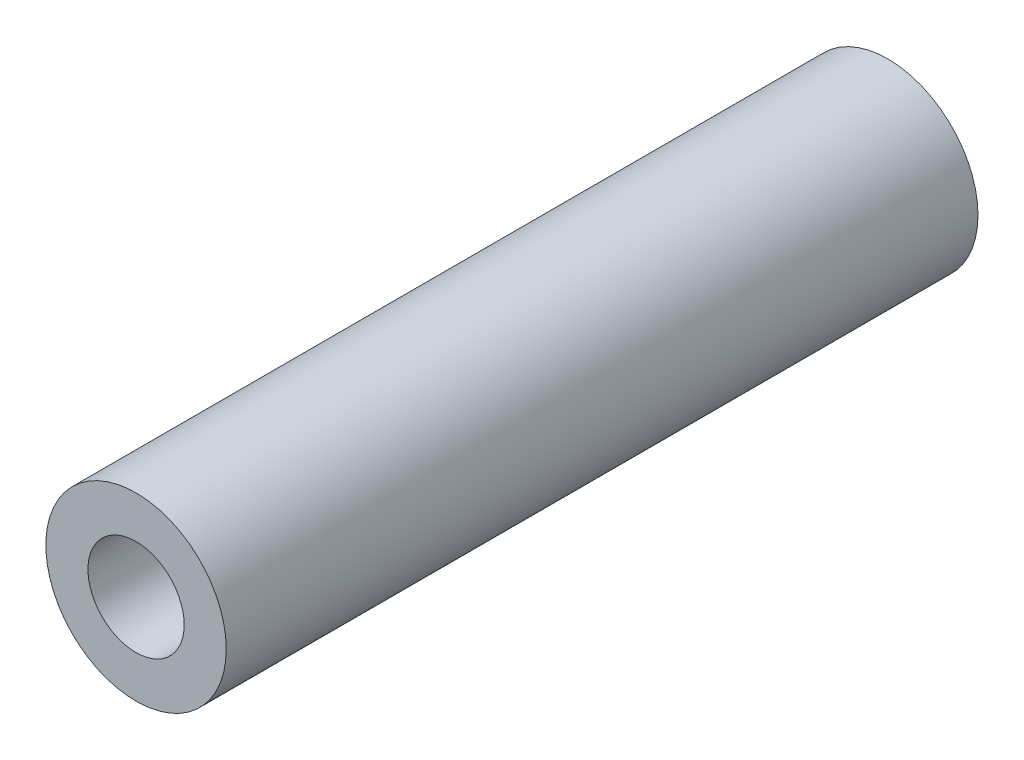
SolidWorks part; units mm, degrees
ref_plane "前视基准面" through (0, 0, 0) normal (0, 0, 1) x (1, 0, 0)
ref_plane "上视基准面" through (0, 0, 0) normal (0, 1, 0) x (1, 0, 0)
ref_plane "右视基准面" through (0, 0, 0) normal (1, 0, 0) x (0, 0, -1)
sketch "草图1" plane through (0, 0, 0) normal (0, 0, 1) x (1, 0, 0)
  circle A0 centre (0, 0) radius 1.6
  circle A1 centre (0, 0) radius 3
  dimension "D1" = 3.2
  dimension "D2" = 6
extrude "凸台-拉伸1" add sketch "草图1" along normal blind 25
